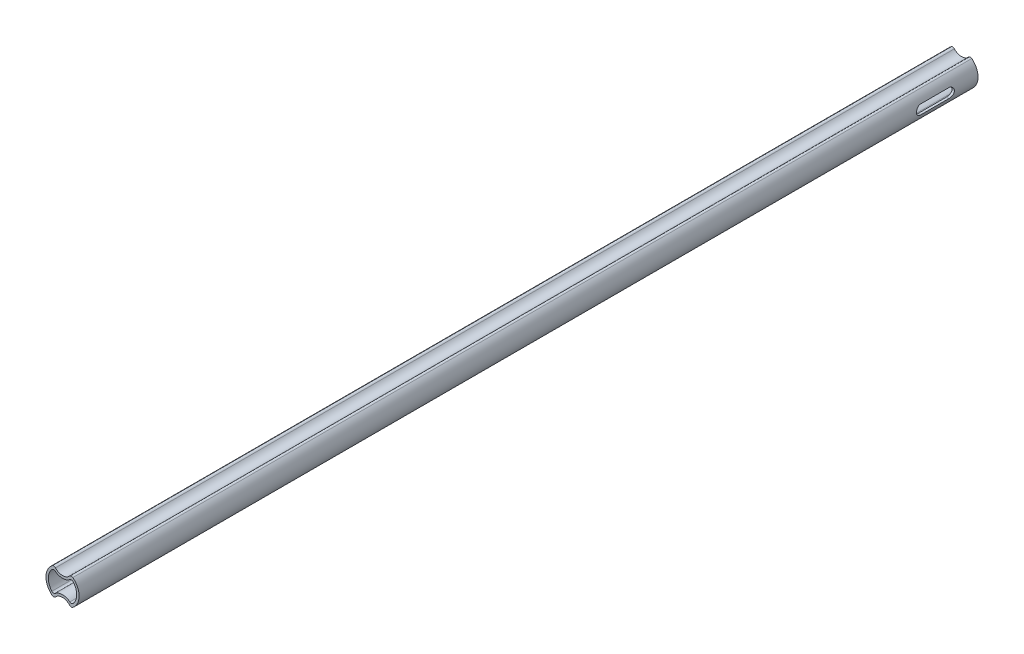
SolidWorks part; units mm, degrees
ref_plane "Piano frontale" through (0, 0, 0) normal (0, 0, 1) x (1, 0, 0)
ref_plane "Piano superiore" through (0, 0, 0) normal (0, 1, 0) x (1, 0, 0)
ref_plane "Piano destro" through (0, 0, 0) normal (1, 0, 0) x (0, 0, -1)
sketch "Schizzo1" plane through (0, 0, 0) normal (0, 0, 1) x (1, 0, 0)
  line L0 (-5.1555, 0) -> (5.3582, 0) construction
  line L1 (0, -55) -> (0, 55) construction
  arc A0 (2.1848, -2.7344) -> (1.4981, -2.675) centre (1.8727, -2.3438) cw
  arc A1 (-2.1848, -2.7344) -> (-1.4981, -2.675) centre (-1.8727, -2.3438) ccw
  arc A2 (-1.4981, -2.675) -> (1.4981, -2.675) centre (0, -4) cw
  arc A3 (2.1848, -2.7344) -> (2.1848, 2.7344) centre (0, 0) ccw
  arc A4 (-2.2472, 1.9875) -> (-2.2472, -1.9875) centre (0, 0) ccw
  arc A5 (1.8727, -2.3438) -> (1.8727, 2.3438) centre (0, 0) ccw construction
  arc A6 (-1.5605, -2.0469) -> (1.5605, -2.0469) centre (0, -4) cw
  arc A7 (-1.8727, 2.3438) -> (1.8727, 2.3438) centre (0, 4) ccw construction
  arc A8 (2.2472, -1.9875) -> (2.2472, 1.9875) centre (0, 0) ccw
  arc A9 (-1.5605, 2.0469) -> (-2.2472, 1.9875) centre (-1.8727, 1.6562) ccw
  arc A10 (-1.5605, 2.0469) -> (1.5605, 2.0469) centre (0, 4) ccw
  arc A12 (-1.8727, 2.3438) -> (-1.8727, -2.3437) centre (0, 0) ccw construction
  arc A13 (-1.8727, -2.3437) -> (1.8727, -2.3438) centre (0, -4) cw construction
  arc A14 (-2.2472, -1.9875) -> (-1.5605, -2.0469) centre (-1.8727, -1.6562) ccw
  arc A16 (2.2472, -1.9875) -> (1.5605, -2.0469) centre (1.8727, -1.6563) cw
  arc A17 (2.2472, 1.9875) -> (1.5605, 2.0469) centre (1.8727, 1.6563) ccw
  arc A25 (-2.1848, 2.7344) -> (-2.1848, -2.7344) centre (0, 0) ccw
  arc A27 (-1.4981, 2.675) -> (1.4981, 2.675) centre (0, 4) ccw
  arc A28 (-2.1848, 2.7344) -> (-1.4981, 2.675) centre (-1.8727, 2.3438) cw
  arc A29 (2.1848, 2.7344) -> (1.4981, 2.675) centre (1.8727, 2.3438) ccw
  arc A32 (-1.8727, -2.3437) -> (-1.8727, -2.3437) centre (-1.8727, -2.3437) ccw construction
  arc A33 (1.8727, -2.3438) -> (1.8727, -2.3438) centre (1.8727, -2.3438) cw construction
  arc A34 (1.8727, 2.3438) -> (1.8727, 2.3438) centre (1.8727, 2.3438) ccw construction
  arc A35 (-1.8727, 2.3438) -> (-1.8727, 2.3438) centre (-1.8727, 2.3438) cw construction
  point P0 (0, 0)
  point P6 (1.4907, 3.1667)
  point P10 (-1.4907, 3.1667)
  point P12 (1.4907, -3.1667)
  point P15 (-1.4907, -3.1667)
  dimension "D1" = 0.5
  dimension "D2" = 0.5
  dimension "D3" = 2.5
  dimension "D6" = 2.0469
  dimension "D7" = 0.5
  dimension "D5" = 3
  dimension "D8" = 1.9875
extrude "Estrusione-Estrusione1" add sketch "Schizzo1" along normal blind 190
sketch "Schizzo2" plane through (0, 0, 0) normal (1, 0, 0) x (0, 0, -1)
  line L0 (3.85, 0) -> (-3.85, 0) construction
  line L1 (-149.5, 0.5) -> (-130.5, 0.5)
  line L2 (0, 3.1281) -> (0, -3.1281) construction
  line L3 (-149.5, -0.5) -> (-130.5, -0.5)
  arc A0 (-149.5, 0.5) -> (-149.5, -0.5) centre (-149.5, 0) ccw
  arc A1 (-130.5, -0.5) -> (-130.5, 0.5) centre (-130.5, 0) ccw
  dimension "D1" = 19
  dimension "D2" = 1
  dimension "D3" = 130.5
extrude "Taglio-Estrusione1" cut sketch "Schizzo2" against normal blind 190 contours L1 A1 L3 A0
sketch "Schizzo3" plane through (0, 0, 0) normal (1, 0, 0) x (0, 0, -1)
  line L0 (0, 3.1281) -> (0, -3.1281) construction
  line L1 (-12, 1) -> (-6, 1)
  line L2 (3.85, 0) -> (-3.85, 0) construction
  line L3 (-12, -1) -> (-6, -1)
  arc A0 (-12, 1) -> (-12, -1) centre (-12, 0) ccw
  arc A1 (-6, -1) -> (-6, 1) centre (-6, 0) ccw
  dimension "D1" = 2
  dimension "D2" = 6
  dimension "D3" = 6
extrude "Taglio-Estrusione2" cut sketch "Schizzo3" along normal through all
